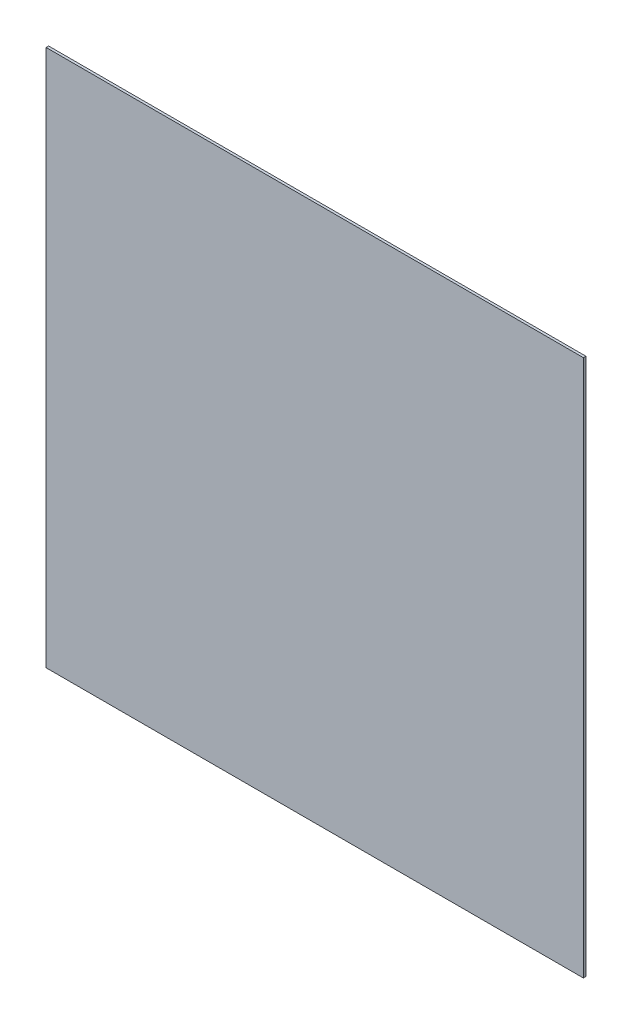
SolidWorks part; units mm, degrees
material "AISI 4130 Steel, normalized at 870C"
ref_plane "Front Plane" through (0, 0, 0) normal (0, 0, 1) x (1, 0, 0)
ref_plane "Top Plane" through (0, 0, 0) normal (0, 1, 0) x (1, 0, 0)
ref_plane "Right Plane" through (0, 0, 0) normal (1, 0, 0) x (0, 0, -1)
sketch "Sketch2" plane through (0, 0, 0) normal (0, 0, 1) x (1, 0, 0)
  line L1 (-160, 160) -> (160, 160)
  line L2 (-160, 160) -> (-160, -160)
  line L3 (-160, -160) -> (160, -160)
  line L4 (160, 160) -> (160, -160)
  dimension "D1" = 320
  dimension "D2" = 320
  dimension "D3" = 160
  dimension "D4" = 160
extrude "Boss-Extrude2" add sketch "Sketch2" along normal blind 1.5
